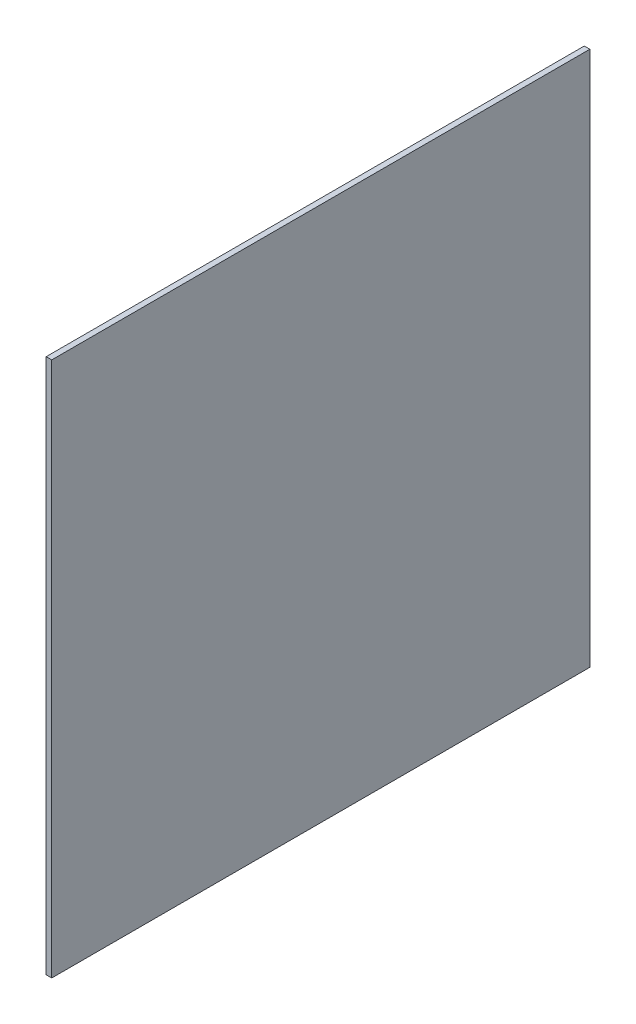
SolidWorks part; units mm, degrees
ref_plane "Front Plane" through (0, 0, 0) normal (0, 0, 1) x (1, 0, 0)
ref_plane "Top Plane" through (0, 0, 0) normal (0, 1, 0) x (1, 0, 0)
ref_plane "Right Plane" through (0, 0, 0) normal (1, 0, 0) x (0, 0, -1)
sketch "Sketch2" plane through (0, 0, 0) normal (1, 0, 0) x (0, 0, -1)
  line L0 (38.2585, -120.5299) -> (231.2585, -120.5299)
  line L1 (231.2585, -120.5299) -> (231.2585, -312.5299)
  line L2 (231.2585, -312.5299) -> (38.2585, -312.5299)
  line L3 (38.2585, -312.5299) -> (38.2585, -120.5299)
  dimension "D1" = 193
  dimension "D2" = 192
extrude "Boss-Extrude2" add sketch "Sketch2" along normal blind 2
